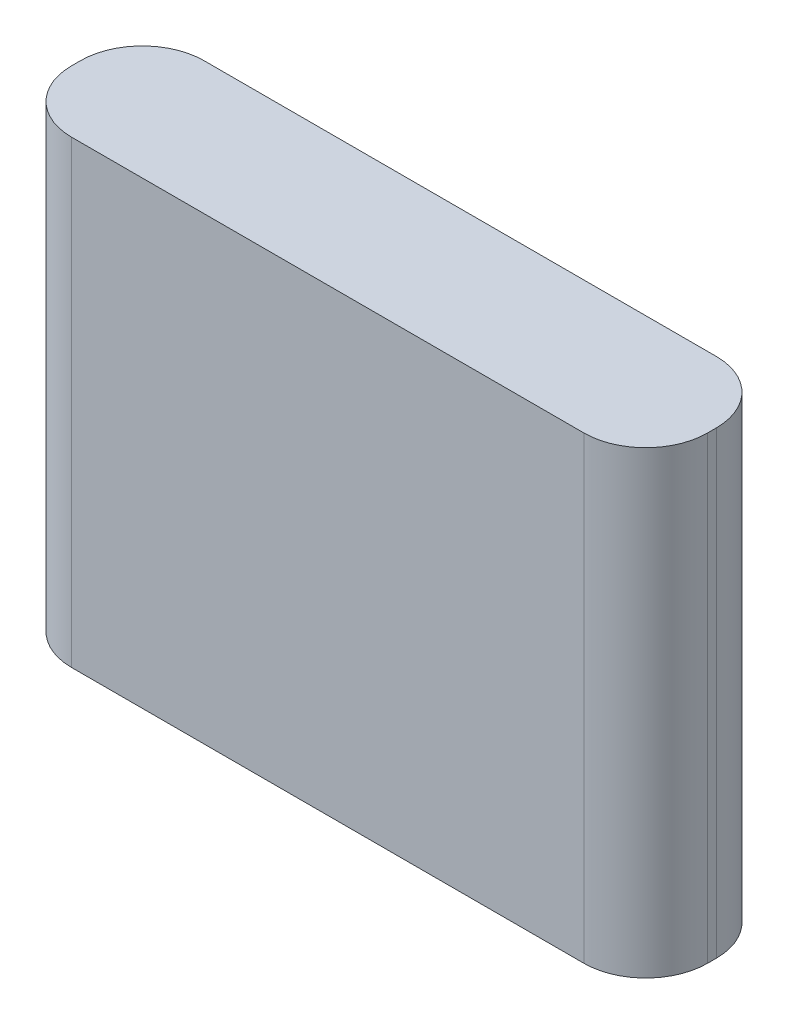
SolidWorks part; units mm, degrees
ref_plane "Plan de face" through (0, 0, 0) normal (0, 0, 1) x (1, 0, 0)
ref_plane "Plan de dessus" through (0, 0, 0) normal (0, 1, 0) x (1, 0, 0)
ref_plane "Plan de droite" through (0, 0, 0) normal (1, 0, 0) x (0, 0, -1)
sketch "Esquisse1" plane through (0, 0, 0) normal (0, 0, 1) x (1, 0, 0)
  line L1 (0, 0) -> (72, 0)
  line L2 (0, 0) -> (0, 52)
  line L3 (0, 52) -> (72, 52)
  line L4 (72, 0) -> (72, 52)
  dimension "D1" = 52
  dimension "D2" = 72
extrude "Boss.-Extru.1" add sketch "Esquisse1" along normal blind 15
fillet "Congé1" radius 7 4 edges at (0, 26, 0) (0, 26, 15) (72, 26, 0) (72, 26, 15)
